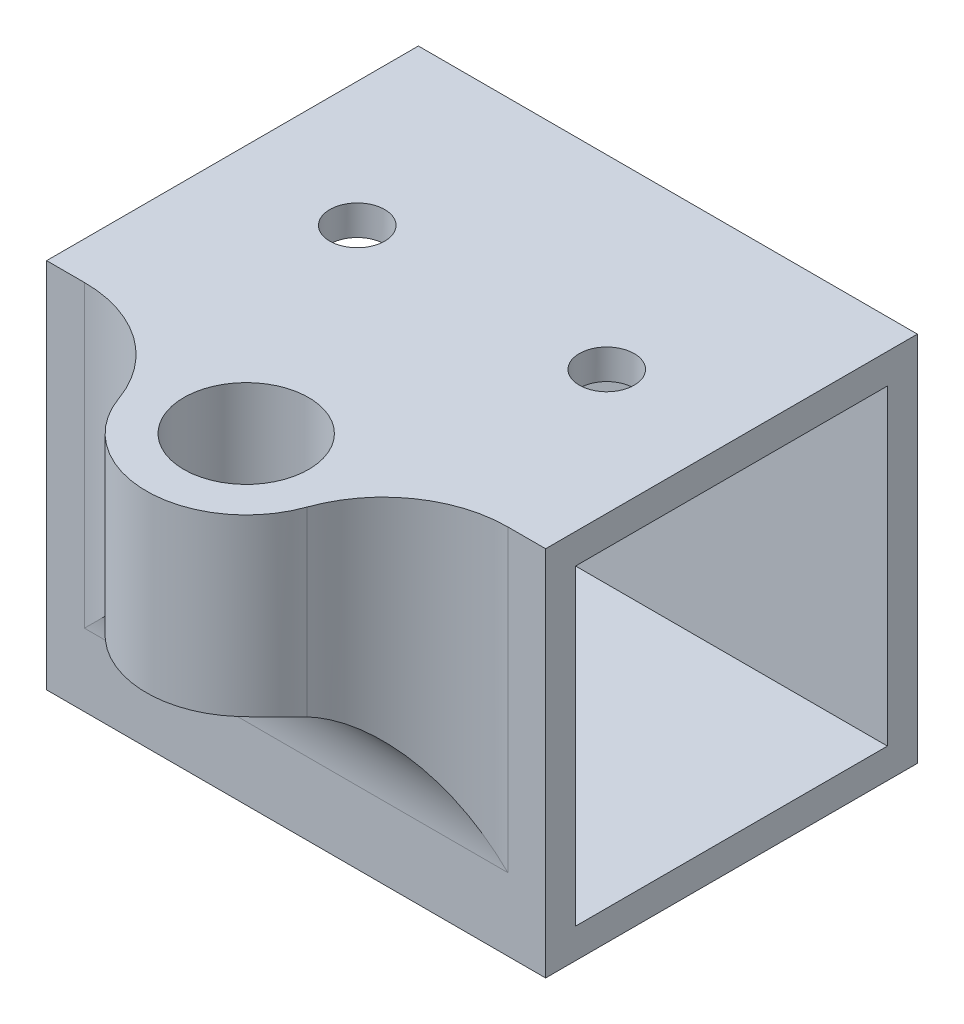
SolidWorks part; units mm, degrees
ref_plane "Front" through (0, 0, 0) normal (0, 0, 1) x (1, 0, 0)
ref_plane "Top" through (0, 0, 0) normal (0, 1, 0) x (1, 0, 0)
ref_plane "Right" through (0, 0, 0) normal (1, 0, 0) x (0, 0, -1)
sketch "Эскиз1" plane through (0, 0, 0) normal (1, 0, 0) x (0, 0, -1)
  line L1 (-12.5, -12.5) -> (12.5, -12.5)
  line L2 (-12.5, -12.5) -> (-12.5, 12.5)
  line L3 (-12.5, 12.5) -> (12.5, 12.5)
  line L4 (12.5, -12.5) -> (12.5, 12.5)
  line L5 (-12.5, -12.5) -> (12.5, 12.5) construction
  line L6 (-12.5, 12.5) -> (12.5, -12.5) construction
  point P0 (0, 0)
  dimension "D1" = 25
  dimension "D2" = 25
extrude "Вытянуть-Тонкостенный1" add sketch "Эскиз1" along normal blind 40 thin
sketch "Эскиз2" plane through (0, 14.9, 0) normal (0, 1, 0) x (1, 0, 0)
  line L0 (20, 14.9) -> (20, -40.7195) construction
  line L1 (40, 14.9) -> (0, 14.9) construction
  line L2 (40, -14.9) -> (0, -14.9) construction
  circle A0 centre (20, -18.9) radius 5
  circle A1 centre (20, -18.9) radius 8
  dimension "D1" = 4
extrude "Бобышка-Вытянуть1" add sketch "Эскиз2" against normal blind 10
sketch "Эскиз3" plane through (0, 4.9, 0) normal (0, -1, 0) x (1, 0, 0)
  circle A0 centre (20, 18.9) radius 8
extrude "Бобышка-Вытянуть2" add sketch "Эскиз3" along normal blind 4
fillet "Скругление1" radius 10 3 edges at (20, 0.9, 14.9) (13.0718, 7.9, 14.9) (26.9282, 7.9, 14.9)
sketch "Эскиз4" plane through (0, 14.9, 0) normal (0, 1, 0) x (1, 0, 0)
  line L0 (0, 0) -> (40, 0) construction
  line L1 (40, 14.9) -> (40, -14.9) construction
  line L2 (0, 14.9) -> (0, -14.9) construction
  circle A0 centre (10, 0) radius 2.2
  circle A1 centre (30, 0) radius 2.2
  dimension "D1" = 10
  dimension "D2" = 10
extrude "Вырез-Вытянуть1" cut sketch "Эскиз4" against normal up to next
sketch "Эскиз5" plane through (0, 14.9, 0) normal (0, 1, 0) x (1, 0, 0)
  circle A0 centre (20, -18.9) radius 5
extrude "Вырез-Вытянуть2" cut sketch "Эскиз5" against normal up to surface (10 mm away) up to face at (20, 4.9, 19.4)
sketch "Эскиз6" plane through (40, 0, 0) normal (1, 0, 0) x (0, 0, -1)
  line L0 (12.5, -12.5) -> (12.5, 12.5) construction
  line L1 (-12.5, 12.5) -> (12.5, 12.5)
  line L2 (-12.5, 12.5) -> (-12.5, -12.5)
  line L3 (-12.5, -12.5) -> (12.5, -12.5)
  line L4 (12.5, 12.5) -> (12.5, -12.5)
  line L5 (-12.5, -12.5) -> (12.5, -12.5) construction
extrude "Вырез-Вытянуть3" cut sketch "Эскиз6" against normal up to next
sketch "Эскиз7" plane through (0, -14.9, 0) normal (0, -1, 0) x (1, 0, 0)
  line L0 (40, -14.9) -> (0, -14.9) construction
  circle A0 centre (20, -17.9) radius 1.2
  circle A1 centre (20, -17.9) radius 3.2
  dimension "D1" = 3
extrude "Бобышка-Вытянуть3" add sketch "Эскиз7" against normal blind 4
fillet "Скругление2" radius 10 2 edges at (18.8864, -12.9, -14.9) (21.1136, -12.9, -14.9)
